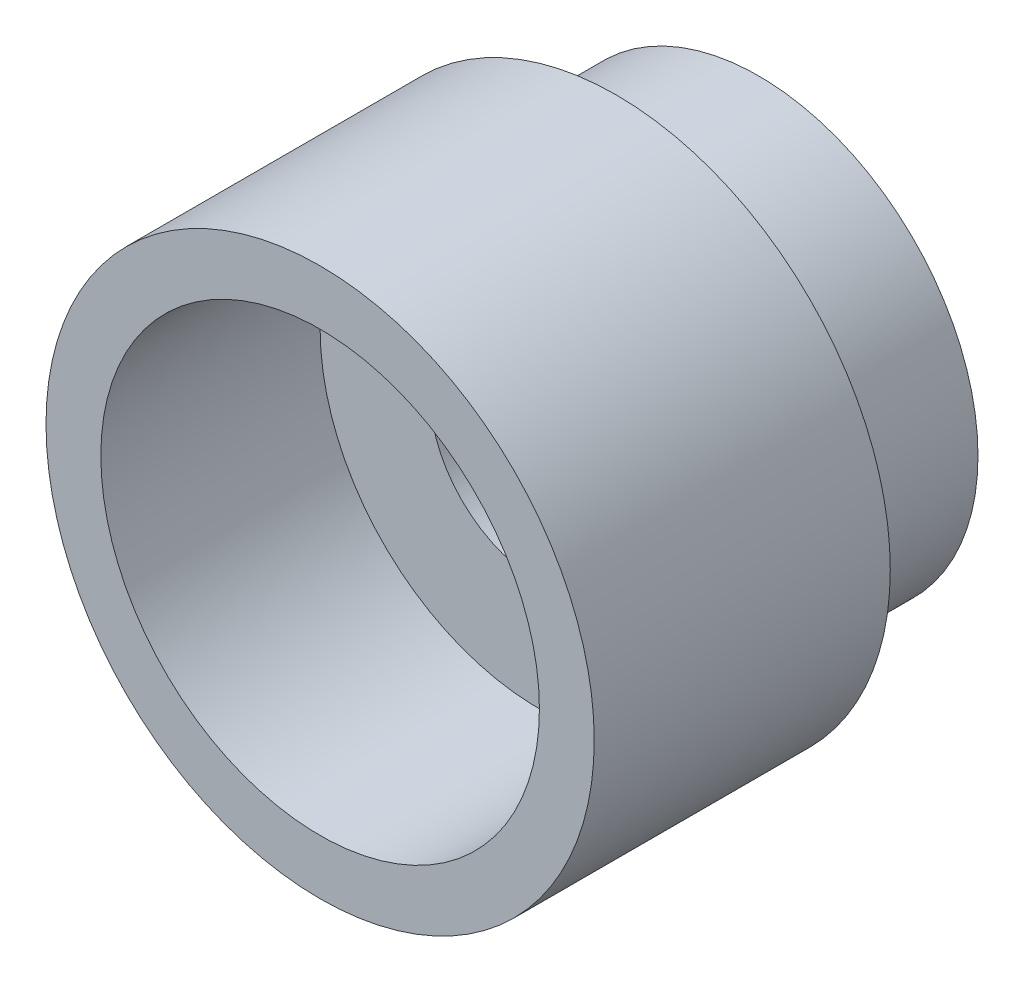
SolidWorks part; units mm, degrees
ref_plane "Front Plane" through (0, 0, 0) normal (0, 0, 1) x (1, 0, 0)
ref_plane "Top Plane" through (0, 0, 0) normal (0, 1, 0) x (1, 0, 0)
ref_plane "Right Plane" through (0, 0, 0) normal (1, 0, 0) x (0, 0, -1)
sketch "Sketch1" plane through (0, 0, 0) normal (1, 0, 0) x (0, 0, -1)
  line L0 (-114.968, 0) -> (-110.968, 0) construction
  line L1 (55, 0) -> (-55, 0) construction
  line L2 (0, 55) -> (0, -55) construction
  line L3 (0, 2.5) -> (2.7, 2.5)
  line L4 (2.7, 2.5) -> (2.7, 2)
  line L5 (2.7, 2) -> (4, 2)
  line L6 (4, 2) -> (4, 1)
  line L7 (4, 1) -> (2, 1)
  line L8 (2, 1) -> (2, 2)
  line L9 (2, 2) -> (0, 2)
  line L10 (0, 2) -> (0, 2.5)
  dimension "D1" = 5
  dimension "D2" = 4
  dimension "D3" = 2
  dimension "D4" = 0.7
  dimension "D5" = 2
  dimension "D6" = 1
  dimension "D7" = 1
revolve "Revolve1" add sketch "Sketch1" angle 360 about L0
